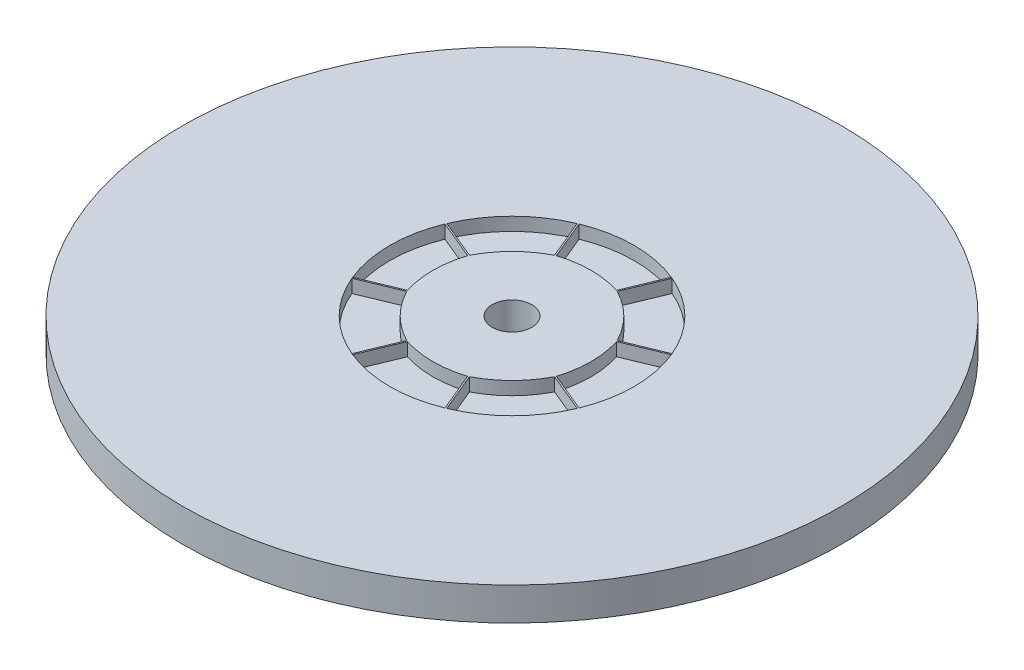
SolidWorks part; units mm, degrees
material "AISI 316 Stainless Steel Sheet (SS)"
ref_plane "Front Plane" through (0, 0, 0) normal (0, 0, 1) x (1, 0, 0)
ref_plane "Top Plane" through (0, 0, 0) normal (0, 1, 0) x (1, 0, 0)
ref_plane "Right Plane" through (0, 0, 0) normal (1, 0, 0) x (0, 0, -1)
sketch "Sketch1" plane through (0, 0, 0) normal (1, 0, 0) x (0, 0, -1)
  line L0 (0, 285.5556) -> (0, 25) construction
  line L1 (-500, 25) -> (-500, -25)
  line L2 (-500, 25) -> (-30, 25)
  line L3 (-500, -25) -> (-30, -25)
  line L4 (0, 25) -> (0, -25) construction
  line L5 (-30, 25) -> (-30, -25)
  line L6 (-30, -25) -> (0, -25) construction
  line L7 (0, 25) -> (0, -25) construction
  line L8 (0, -25) -> (0, -214.4444) construction
  line L9 (-30, 25) -> (0, 25) construction
  point P5 (-500, 0)
  dimension "D1" = 1000
  dimension "D2" = 50
  dimension "D3" = 30
revolve "Revolve1" add sketch "Sketch1" angle 360 about L0
sketch "Sketch2" plane through (0, -25, 0) normal (0, -1, 0) x (1, 0, 0)
  line L0 (0, 0) -> (0, 604.4151) construction
  line L1 (-180, 446.4762) -> (-122.573, 307.8351)
  line L2 (122.573, 307.8351) -> (180, 446.4762)
  line L3 (188.4271, 442.9855) -> (131.0001, 304.3445)
  line L4 (304.3445, 131.0001) -> (442.9855, 188.4271)
  line L5 (446.4762, 180) -> (307.8351, 122.573)
  line L6 (307.8351, -122.573) -> (446.4762, -180)
  line L7 (442.9855, -188.4271) -> (304.3445, -131.0001)
  line L8 (131.0001, -304.3445) -> (188.4271, -442.9855)
  line L9 (180, -446.4762) -> (122.573, -307.8351)
  line L10 (-122.573, -307.8351) -> (-180, -446.4762)
  line L11 (-188.4271, -442.9855) -> (-131.0001, -304.3445)
  line L12 (-304.3445, -131.0001) -> (-442.9855, -188.4271)
  line L13 (-446.4762, -180) -> (-307.8351, -122.573)
  line L14 (-307.8351, 122.573) -> (-446.4762, 180)
  line L15 (-442.9855, 188.4271) -> (-304.3445, 131.0001)
  line L16 (-131.0001, 304.3445) -> (-188.4271, 442.9855)
  arc A1 (-122.573, 307.8351) -> (122.573, 307.8351) centre (0, -20) cw
  arc A2 (180, 446.4762) -> (-180, 446.4762) centre (0, -20) ccw
  arc A3 (442.9855, 188.4271) -> (188.4271, 442.9855) centre (-14.1421, -14.1421) ccw
  arc A4 (131.0001, 304.3445) -> (304.3445, 131.0001) centre (-14.1421, -14.1421) cw
  arc A5 (446.4762, -180) -> (446.4762, 180) centre (-20, 0) ccw
  arc A6 (307.8351, 122.573) -> (307.8351, -122.573) centre (-20, 0) cw
  arc A7 (188.4271, -442.9855) -> (442.9855, -188.4271) centre (-14.1421, 14.1421) ccw
  arc A8 (304.3445, -131.0001) -> (131.0001, -304.3445) centre (-14.1421, 14.1421) cw
  arc A9 (-180, -446.4762) -> (180, -446.4762) centre (0, 20) ccw
  arc A10 (122.573, -307.8351) -> (-122.573, -307.8351) centre (0, 20) cw
  arc A11 (-442.9855, -188.4271) -> (-188.4271, -442.9855) centre (14.1421, 14.1421) ccw
  arc A12 (-131.0001, -304.3445) -> (-304.3445, -131.0001) centre (14.1421, 14.1421) cw
  arc A13 (-446.4762, 180) -> (-446.4762, -180) centre (20, 0) ccw
  arc A14 (-307.8351, -122.573) -> (-307.8351, 122.573) centre (20, 0) cw
  arc A15 (-188.4271, 442.9855) -> (-442.9855, 188.4271) centre (14.1421, -14.1421) ccw
  arc A16 (-304.3445, 131.0001) -> (-131.0001, 304.3445) centre (14.1421, -14.1421) cw
  point P46 (0, 0)
  dimension "D1" = 500
  dimension "D2" = 350
  dimension "D3" = 45
  dimension "D4" = 360
  dimension "D5" = 20
  dimension "D6" = 8
extrude "Cut-Extrude1" cut sketch "Sketch2" against normal blind 20
sketch "Sketch3" plane through (0, 25, 0) normal (0, 1, 0) x (1, 0, 0)
  line L0 (0, 0) -> (0, 210.2358) construction
  line L1 (-45.6324, 112.8905) -> (-70, 171.719)
  line L2 (45.6324, 112.8905) -> (70, 171.719)
  line L3 (112.0926, 47.5586) -> (170.9212, 71.9262)
  line L4 (47.5586, 112.0926) -> (71.9262, 170.9212)
  line L5 (112.8905, -45.6324) -> (171.719, -70)
  line L6 (112.8905, 45.6324) -> (171.719, 70)
  line L7 (47.5586, -112.0926) -> (71.9262, -170.9212)
  line L8 (112.0926, -47.5586) -> (170.9212, -71.9262)
  line L9 (-45.6324, -112.8905) -> (-70, -171.719)
  line L10 (45.6324, -112.8905) -> (70, -171.719)
  line L11 (-112.0926, -47.5586) -> (-170.9212, -71.9262)
  line L12 (-47.5586, -112.0926) -> (-71.9262, -170.9212)
  line L13 (-112.8905, 45.6324) -> (-171.719, 70)
  line L14 (-112.8905, -45.6324) -> (-171.719, -70)
  line L15 (-47.5586, 112.0926) -> (-71.9262, 170.9212)
  line L16 (-112.0926, 47.5586) -> (-170.9212, 71.9262)
  arc A0 (-70, 171.719) -> (70, 171.719) centre (0, -120) cw construction
  arc A1 (-45.6324, 112.8905) -> (45.6324, 112.8905) centre (0, -30) cw
  arc A2 (71.9262, 170.9212) -> (170.9212, 71.9262) centre (-84.8528, -84.8528) cw construction
  arc A3 (47.5586, 112.0926) -> (112.0926, 47.5586) centre (-21.2132, -21.2132) cw
  arc A4 (171.719, 70) -> (171.719, -70) centre (-120, 0) cw construction
  arc A5 (112.8905, 45.6324) -> (112.8905, -45.6324) centre (-30, 0) cw
  arc A6 (170.9212, -71.9262) -> (71.9262, -170.9212) centre (-84.8528, 84.8528) cw construction
  arc A7 (112.0926, -47.5586) -> (47.5586, -112.0926) centre (-21.2132, 21.2132) cw
  arc A8 (70, -171.719) -> (-70, -171.719) centre (0, 120) cw construction
  arc A9 (45.6324, -112.8905) -> (-45.6324, -112.8905) centre (0, 30) cw
  arc A10 (-71.9262, -170.9212) -> (-170.9212, -71.9262) centre (84.8528, 84.8528) cw construction
  arc A11 (-47.5586, -112.0926) -> (-112.0926, -47.5586) centre (21.2132, 21.2132) cw
  arc A12 (-171.719, -70) -> (-171.719, 70) centre (120, 0) cw construction
  arc A13 (-112.8905, -45.6324) -> (-112.8905, 45.6324) centre (30, 0) cw
  arc A14 (-170.9212, 71.9262) -> (-71.9262, 170.9212) centre (84.8528, -84.8528) cw construction
  arc A15 (-112.0926, 47.5586) -> (-47.5586, 112.0926) centre (21.2132, -21.2132) cw
  circle A16 centre (0, 0) radius 30 construction
  arc A17 (-171.719, 70) -> (-171.719, -70) centre (0, 0) ccw
  arc A18 (-71.9262, 170.9212) -> (-170.9212, 71.9262) centre (0, 0) ccw
  arc A19 (70, 171.719) -> (-70, 171.719) centre (0, 0) ccw
  arc A20 (170.9212, 71.9262) -> (71.9262, 170.9212) centre (0, 0) ccw
  arc A21 (171.719, -70) -> (171.719, 70) centre (0, 0) ccw
  arc A22 (71.9262, -170.9212) -> (170.9212, -71.9262) centre (0, 0) ccw
  arc A23 (-70, -171.719) -> (70, -171.719) centre (0, 0) ccw
  arc A24 (-170.9212, -71.9262) -> (-71.9262, -170.9212) centre (0, 0) ccw
  point P53 (0, 0)
  dimension "D1" = 150
  dimension "D2" = 300
  dimension "D3" = 45
  dimension "D5" = 140
  dimension "D4" = 8
extrude "Cut-Extrude2" cut sketch "Sketch3" against normal blind 20
